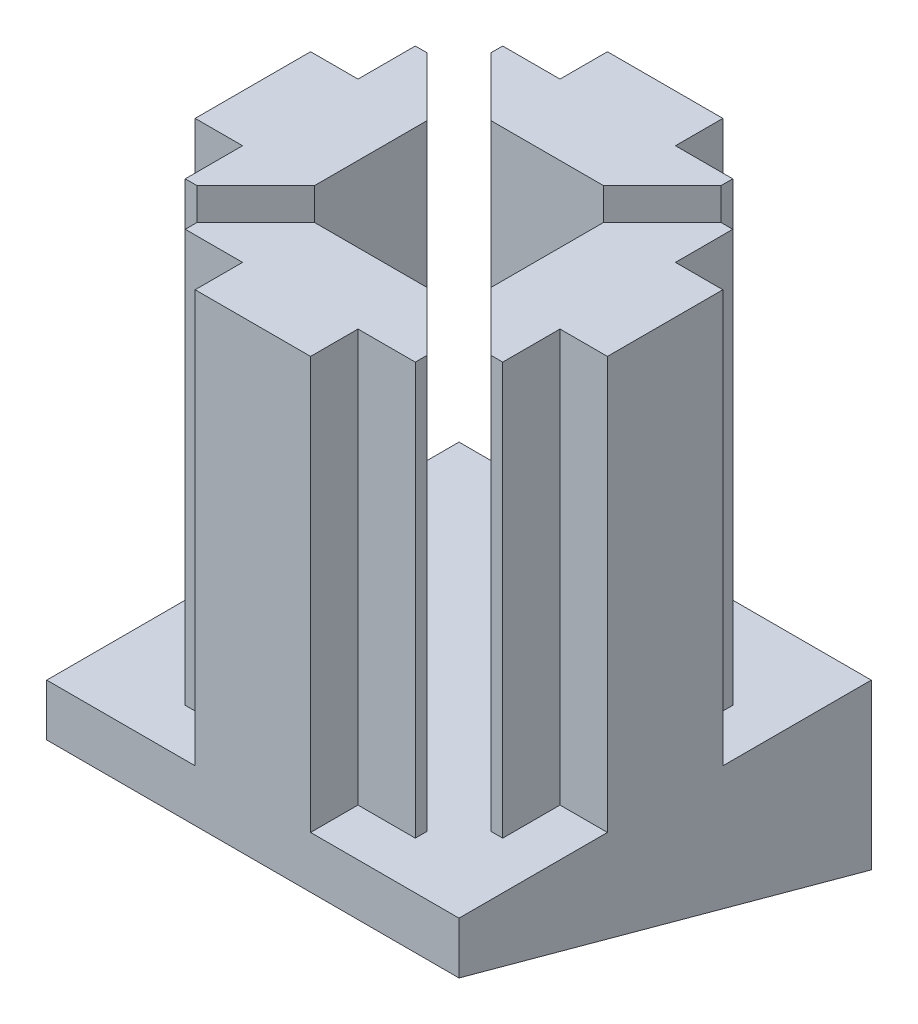
SolidWorks part; units mm, degrees
ref_plane "Front Plane" through (0, 0, 0) normal (0, 0, 1) x (1, 0, 0)
ref_plane "Top Plane" through (0, 0, 0) normal (0, 1, 0) x (1, 0, 0)
ref_plane "Right Plane" through (0, 0, 0) normal (1, 0, 0) x (0, 0, -1)
sketch "Sketch1" plane through (0, 0, 0) normal (0, 1, 0) x (1, 0, 0)
  line L20 (0, 0) -> (50000, 0) construction
  line L21 (-10, -2.8) -> (-10, 49997.2) construction
  line L22 (-10, -2.8) -> (-10, 2.8)
  line L23 (-7.1356, 5.58) -> (-4.28, 2.7244)
  line L24 (-7.7, 5.58) -> (-7.1356, 5.58)
  line L25 (-10, -2.8) -> (-7.7, -2.8)
  line L26 (-4.28, -2.7244) -> (-4.28, 2.7244)
  line L27 (-7.1356, -5.58) -> (-4.28, -2.7244)
  line L28 (-7.7, -5.58) -> (-7.1356, -5.58)
  line L29 (-7.7, -2.8) -> (-7.7, -5.58)
  line L30 (-7.7, 2.8) -> (-7.7, 5.58)
  line L31 (-10, 2.8) -> (-7.7, 2.8)
  line L32 (0, 0) -> (0, -50000) construction
  line L33 (10, 2.8) -> (7.7, 2.8)
  line L34 (7.7, 2.8) -> (7.7, 5.58)
  line L35 (7.7, -2.8) -> (7.7, -5.58)
  line L36 (7.7, -5.58) -> (7.1356, -5.58)
  line L37 (7.1356, -5.58) -> (4.28, -2.7244)
  line L38 (4.28, -2.7244) -> (4.28, 2.7244)
  line L39 (10, -2.8) -> (7.7, -2.8)
  line L40 (7.7, 5.58) -> (7.1356, 5.58)
  line L41 (7.1356, 5.58) -> (4.28, 2.7244)
  line L42 (10, -2.8) -> (10, 2.8)
  line L43 (0, 0) -> (35355.3391, -35355.3391) construction
  line L44 (0, 0) -> (0, -50000) construction
  line L45 (2.8, -10) -> (-2.8, -10)
  line L46 (-5.58, -7.1356) -> (-2.7244, -4.28)
  line L47 (-5.58, -7.7) -> (-5.58, -7.1356)
  line L48 (2.8, -10) -> (2.8, -7.7)
  line L49 (2.7244, -4.28) -> (-2.7244, -4.28)
  line L50 (5.58, -7.1356) -> (2.7244, -4.28)
  line L51 (5.58, -7.7) -> (5.58, -7.1356)
  line L52 (2.8, -7.7) -> (5.58, -7.7)
  line L53 (-2.8, -7.7) -> (-5.58, -7.7)
  line L54 (-2.8, -10) -> (-2.8, -7.7)
  line L55 (-2.8, 10) -> (-2.8, 7.7)
  line L56 (-2.8, 7.7) -> (-5.58, 7.7)
  line L57 (2.8, 7.7) -> (5.58, 7.7)
  line L58 (5.58, 7.7) -> (5.58, 7.1356)
  line L59 (5.58, 7.1356) -> (2.7244, 4.28)
  line L60 (2.7244, 4.28) -> (-2.7244, 4.28)
  line L61 (2.8, 10) -> (2.8, 7.7)
  line L62 (-5.58, 7.7) -> (-5.58, 7.1356)
  line L63 (-5.58, 7.1356) -> (-2.7244, 4.28)
  line L64 (2.8, 10) -> (-2.8, 10)
  point P12 (-4.28, 0)
  point P16 (-10, 0)
  point P28 (10, 0)
  point P29 (4.28, 0)
  point P44 (0, -4.28)
  point P45 (0, -10)
  point P56 (0, 10)
  point P57 (0, 4.28)
  dimension "D1" = 45
extrude "Boss-Extrude1" add sketch "Sketch1" along normal blind 20
sketch "Sketch2" plane through (0, 0, 0) normal (0, -1, 0) x (1, 0, 0)
  line L0 (-10, 10) -> (10, 10)
  line L1 (10, 10) -> (10, -10)
  line L2 (10, -10) -> (-10, -10)
  line L3 (-10, -10) -> (-10, 10)
  line L4 (2.8, -10) -> (-2.8, -10) construction
  line L5 (10, 2.8) -> (10, -2.8) construction
  line L6 (-2.8, 10) -> (2.8, 10) construction
  line L7 (-10, -2.8) -> (-10, 2.8) construction
  point P0 (-10, -9.6197)
extrude "Boss-Extrude2" add sketch "Sketch2" along normal blind 20
sketch "Sketch3" plane through (10, 0, 0) normal (1, 0, 0) x (0, 0, -1)
  line L2 (10.5967, -8.1372) -> (10.5967, -38.3455)
  line L3 (10.5967, -38.3455) -> (-10.4111, -38.3455)
  line L4 (-10.4111, -38.3455) -> (-10.4111, -2.4027)
  line L5 (10.5967, -8.1372) -> (-10.4111, -2.4027)
extrude "Cut-Extrude1" cut sketch "Sketch3" against normal through all
